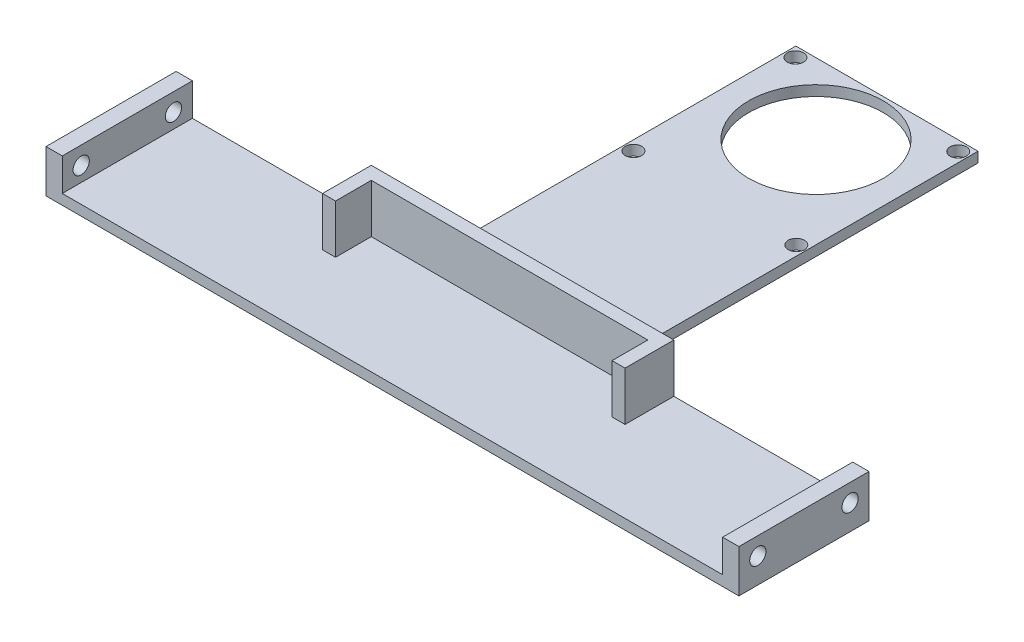
SolidWorks part; units mm, degrees
ref_plane "Front Plane" through (0, 0, 0) normal (0, 0, 1) x (1, 0, 0)
ref_plane "Top Plane" through (0, 0, 0) normal (0, 1, 0) x (1, 0, 0)
ref_plane "Right Plane" through (0, 0, 0) normal (1, 0, 0) x (0, 0, -1)
sketch "Breadboard" plane through (0, 0, 0) normal (0, 1, 0) x (1, 0, 0)
  line L1 (0, 0) -> (53.975, 0) construction
  line L2 (0, 0) -> (0, 165.1) construction
  line L3 (0, 165.1) -> (53.975, 165.1) construction
  line L4 (53.975, 0) -> (53.975, 165.1) construction
  dimension "D1" = 53.975
  dimension "D2" = 165.1
sketch "Camera" plane through (0, 0, 0) normal (0, 1, 0) x (1, 0, 0)
  line L0 (18.2245, 224.917) -> (14.4145, 224.917) construction
  line L1 (18.2245, 233.68) -> (35.7505, 233.68) construction
  line L2 (18.2245, 233.68) -> (18.2245, 216.154) construction
  line L3 (18.2245, 216.154) -> (35.7505, 216.154) construction
  line L5 (18.2245, 223.012) -> (16.3195, 223.012) construction
  line L6 (16.3195, 223.012) -> (18.2245, 223.012) construction
  line L7 (26.9875, 233.68) -> (26.9875, 216.154) construction
  line L10 (18.2245, 233.68) -> (35.7505, 216.154) construction
  line L11 (26.9875, 233.68) -> (26.9875, 238.76) construction
  line L12 (9.2075, 238.76) -> (44.7675, 238.76) construction
  line L13 (9.2075, 238.76) -> (9.2075, 203.2) construction
  line L14 (9.2075, 203.2) -> (44.7675, 203.2) construction
  line L15 (44.7675, 238.76) -> (44.7675, 203.2) construction
  line L16 (16.3195, 226.822) -> (18.2245, 226.822) construction
  line L18 (26.9875, 216.154) -> (26.9875, 203.2) construction
  line L19 (0, 165.1) -> (53.975, 165.1) construction
  line L20 (26.9875, 203.2) -> (26.9875, 165.1) construction
  line L21 (18.2245, 233.68) -> (18.2245, 226.822)
  line L22 (18.2245, 226.822) -> (16.3195, 226.822)
  line L23 (35.7505, 223.012) -> (35.7505, 216.154)
  line L24 (37.6555, 223.012) -> (35.7505, 223.012)
  line L25 (35.7505, 226.822) -> (37.6555, 226.822)
  line L26 (16.3195, 223.012) -> (18.2245, 223.012)
  line L27 (18.2245, 223.012) -> (18.2245, 216.154)
  line L28 (35.7505, 233.68) -> (35.7505, 226.822)
  line L29 (18.2245, 233.68) -> (35.7505, 233.68)
  line L30 (35.7505, 216.154) -> (18.2245, 216.154)
  circle A0 centre (16.3195, 224.917) radius 1.905 construction
  arc A2 (16.3195, 226.822) -> (16.3195, 223.012) centre (16.3195, 224.917) ccw
  arc A3 (37.6555, 226.822) -> (37.6555, 223.012) centre (37.6555, 224.917) cw
  point P4 (18.2245, 224.917)
  point P12 (26.9875, 238.76)
  point P35 (26.9875, 165.1)
  dimension "D1" = 17.526
  dimension "D2" = 17.526
  dimension "D3" = 3.81
  dimension "D4" = 35.56
  dimension "D5" = 35.56
  dimension "D6" = 5.08
  dimension "D7" = 38.1
sketch "Sketch1" plane through (0, 0, 0) normal (0, 1, 0) x (1, 0, 0)
  line L6 (-2.54, 167.64) -> (-2.54, 158.115)
  line L7 (-2.54, 167.64) -> (56.515, 167.64)
  line L8 (56.515, 167.64) -> (56.515, 158.115)
  line L9 (56.515, 167.64) -> (56.515, 0)
  line L10 (-2.54, 167.64) -> (56.515, 167.64)
  line L11 (-2.54, 0) -> (-2.54, 167.64)
  line L12 (56.515, 167.64) -> (56.515, 0) construction
  line L13 (-2.54, 167.64) -> (56.515, 167.64) construction
  line L14 (-2.54, 0) -> (-2.54, 167.64) construction
  line L15 (-2.54, 158.115) -> (0, 158.115)
  line L16 (0, 0) -> (0, 165.1) construction
  line L17 (0, 158.115) -> (0, 165.1)
  line L18 (0, 165.1) -> (53.975, 165.1)
  line L19 (53.975, 165.1) -> (53.975, 158.115)
  line L20 (53.975, 0) -> (53.975, 165.1) construction
  line L21 (53.975, 158.115) -> (56.515, 158.115)
  dimension "D2" = 9.525
  dimension "D1" = 2.54
sketch "Sketch2" plane through (0, 0, 0) normal (0, 1, 0) x (1, 0, 0)
  line L0 (-2.54, 142.24) -> (56.515, 142.24)
  line L1 (56.515, 142.24) -> (56.515, 167.64)
  line L2 (56.515, 167.64) -> (-2.54, 167.64)
  line L3 (-2.54, 167.64) -> (-2.54, 142.24)
  dimension "D1" = 25.4
extrude "Boss-Extrude1" add sketch "Sketch2" along normal blind 2
extrude "Boss-Extrude2" add sketch "Sketch1" along normal blind 9.525 from surface at 2 starting at face at (26.9875, 2, -154.94)
sketch "Sketch3" plane through (0, 0, 0) normal (0, 1, 0) x (1, 0, 0)
  line L0 (56.515, 167.64) -> (56.515, 142.24)
  line L1 (56.515, 167.64) -> (94.615, 167.64)
  line L2 (94.615, 167.64) -> (94.615, 142.24)
  line L3 (94.615, 142.24) -> (56.515, 142.24)
  dimension "D1" = 38.1
extrude "Boss-Extrude3" add sketch "Sketch3" along normal up to vertex
sketch "Sketch4" plane through (0, 0, 0) normal (0, 1, 0) x (1, 0, 0)
  line L0 (94.615, 167.64) -> (56.515, 167.64) construction
  line L1 (91.44, 167.64) -> (94.615, 167.64)
  line L2 (91.44, 167.64) -> (91.44, 142.24)
  line L3 (91.44, 142.24) -> (94.615, 142.24)
  line L4 (94.615, 167.64) -> (94.615, 142.24)
  dimension "D1" = 3.175
extrude "Boss-Extrude4" add sketch "Sketch4" along normal blind 6.35 from surface at 2 starting at face at (40.513, 2, -158.242)
sketch "Sketch5" plane through (94.615, 0, 0) normal (1, 0, 0) x (0, 0, -1)
  line L0 (142.24, 0) -> (167.64, 0) construction
  line L1 (145.94, 4.896) -> (163.94, 4.896) construction
  line L2 (154.94, 4.896) -> (154.94, 0) construction
  circle A0 centre (145.94, 4.896) radius 1.5875
  circle A1 centre (163.94, 4.896) radius 1.5875
  point P0 (154.94, 0)
  point P6 (154.94, 4.896)
  dimension "D2" = 3.175
  dimension "D1" = 18
extrude "Cut-Extrude1" cut sketch "Sketch5" against normal up to surface (3.175 mm away) up to face at (91.44, 5.175, -154.94)
ref_plane "SymmetryPlane" through (26.9875, 0, 0) normal (1, 0, 0) x (0, 0, -1)
mirror "Mirror1" about plane through (26.9875, 0, 0) normal (1, 0, 0) of bodies 116
sketch "Sketch6" plane through (0, 0, 0) normal (0, 1, 0) x (1, 0, 0)
  line L0 (-2.54, 167.64) -> (56.515, 167.64) construction
  line L1 (9.2075, 238.76) -> (44.7675, 238.76)
  line L2 (9.2075, 238.76) -> (9.2075, 167.64)
  line L3 (9.2075, 167.64) -> (44.7675, 167.64)
  line L4 (44.7675, 238.76) -> (44.7675, 167.64)
  line L5 (49.7299, 238.76) -> (49.7299, 203.2) construction
  line L6 (49.7299, 220.98) -> (9.2075, 220.98) construction
  line L7 (26.9875, 238.76) -> (26.9875, 203.2) construction
  circle A0 centre (11.0905, 236.7839) radius 1.5875
  circle A1 centre (11.0905, 205.1761) radius 1.5875
  circle A2 centre (42.8845, 205.1761) radius 1.5875
  circle A3 centre (42.8845, 236.7839) radius 1.5875
  dimension "D1" = 3.175
extrude "Boss-Extrude5" add sketch "Sketch6" along normal up to vertex (2 mm away)
fillet "Fillet1" radius 2.54 1 edges at (26.9875, 2, -167.64)
sketch "Sketch10" plane through (0, 2, 0) normal (0, 1, 0) x (1, 0, 0)
  line L0 (26.9875, 233.68) -> (26.9875, 216.154) construction
  circle A2 centre (26.9875, 224.917) radius 13.1292
extrude "Cut-Extrude2" cut sketch "Sketch10" against normal up to surface (2 mm away) up to face at (26.9875, 0, -179.07)
equation "\"Camera\"=0.15"
